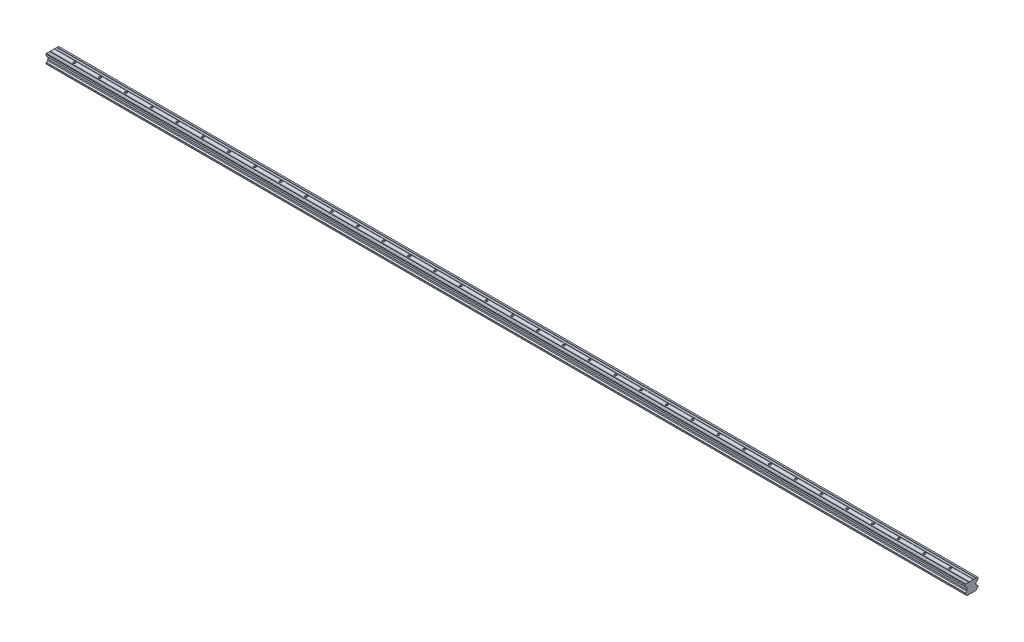
SolidWorks part; units mm, degrees
material "ASTM A36 Steel"
ref_plane "Front Plane" through (0, 0, 0) normal (0, 0, 1) x (1, 0, 0)
ref_plane "Top Plane" through (0, 0, 0) normal (0, 1, 0) x (1, 0, 0)
ref_plane "Right Plane" through (0, 0, 0) normal (1, 0, 0) x (0, 0, -1)
sketch "Sketch1" plane through (0, 0, 0) normal (1, 0, 0) x (0, 0, -1)
  line L0 (-7.9658, -7.694) -> (-7.2663, -8.3935)
  line L1 (-7.2663, -8.3935) -> (7.2663, -8.3935)
  line L2 (7.2663, -8.3935) -> (7.9658, -7.694)
  line L3 (9.7474, -5.9133) -> (10, -5.6608)
  line L4 (10, -5.6608) -> (10, -3.7884)
  line L5 (10, -3.7884) -> (9.7474, -3.5358)
  line L6 (7.9658, -1.7232) -> (7.0051, -0.7626)
  line L7 (7.0051, -0.7626) -> (7.0051, 2.1662)
  line L8 (7.0051, 2.1662) -> (10, 5.1611)
  line L9 (10, 5.1611) -> (10, 7.7124)
  line L10 (10, 7.7124) -> (9.4085, 8.3935)
  line L11 (9.4085, 8.3935) -> (7.133, 8.3935)
  line L12 (7.133, 8.3935) -> (6.7895, 8.05)
  line L13 (6.7895, 8.05) -> (4.2711, 8.05)
  line L14 (4.2711, 8.05) -> (3.9277, 8.3935)
  line L15 (3.9277, 8.3935) -> (3.0613, 8.3935)
  line L16 (3.0613, 8.3935) -> (2.872, 8.2042)
  line L17 (2.872, 8.2042) -> (-2.872, 8.2042)
  line L18 (-2.872, 8.2042) -> (-3.0613, 8.3935)
  line L19 (-3.0613, 8.3935) -> (-3.9277, 8.3935)
  line L20 (-3.9277, 8.3935) -> (-4.2712, 8.05)
  line L21 (-4.2712, 8.05) -> (-6.7895, 8.05)
  line L22 (-6.7895, 8.05) -> (-7.133, 8.3935)
  line L23 (-7.133, 8.3935) -> (-9.3077, 8.3935)
  line L24 (-9.3077, 8.3935) -> (-10, 7.7012)
  line L25 (-10, 7.7012) -> (-10, 5.1611)
  line L26 (-10, 5.1611) -> (-7.0051, 2.1662)
  line L27 (-7.0051, 2.1662) -> (-7.0051, -0.7626)
  line L28 (-7.0051, -0.7626) -> (-7.9658, -1.7232)
  line L29 (-9.7474, -5.9133) -> (-10, -5.6608)
  line L30 (-10, -5.6608) -> (-10, -3.7884)
  line L31 (-10, -3.7884) -> (-9.7474, -3.5358)
  arc A0 (-7.9658, -7.694) -> (-9.7474, -5.9133) centre (-9.7035, -7.6511) ccw
  arc A1 (-9.7474, -3.5358) -> (-7.9658, -1.7232) centre (-9.7025, -1.7981) ccw
  arc A2 (7.9658, -1.7232) -> (9.7474, -3.5358) centre (9.7025, -1.7981) ccw
  arc A3 (9.7474, -5.9133) -> (7.9658, -7.694) centre (9.7035, -7.6511) ccw
extrude "Boss-Extrude1" add sketch "Sketch1" along normal blind 1427
sketch "Sketch2" plane through (0, -8.3935, 0) normal (0, -1, 0) x (1, 0, 0)
  circle A0 centre (34, 0) radius 3
  dimension "D1" = 6
  dimension "D2" = 34
hole_wizard "Hole1" positions "3DSketch1" profile "Sketch3" legacy end condition through all
sketch3d "3DSketch1"
  point P0 (34, -8.3935, 0)
sketch "Sketch3" plane through (34, -8.3935, 0) normal (1, 0, 0) x (0, 0, -1)
  line L0 (0, 0) -> (0, 16.7869)
  line L1 (0, 16.7869) -> (1.75, 16.7869)
  line L2 (1.75, 16.7869) -> (1.75, 4.5)
  line L3 (1.75, 4.5) -> (3, 4.5)
  line L4 (3, 4.5) -> (3, 0)
  line L5 (3, 0) -> (0, 0)
  line L6 (0, 110) -> (0, -10) construction
  dimension "Diameter" = 3.5
  dimension "Depth" = 16.7869
  dimension "C-Bore Diameter" = 6
  dimension "C-Bore Depth" = 4.5
sketch "Sketch4" plane through (0, -8.3935, 0) normal (0, -1, 0) x (-1, 0, 0)
  line L0 (0, 0) -> (-1427, 0) construction
  line L1 (-1427, -7.2663) -> (-1427, 7.2663) construction
pattern_linear "LPattern1" count 35 spacing 40 along (1, 0, 0) of "Hole1"
